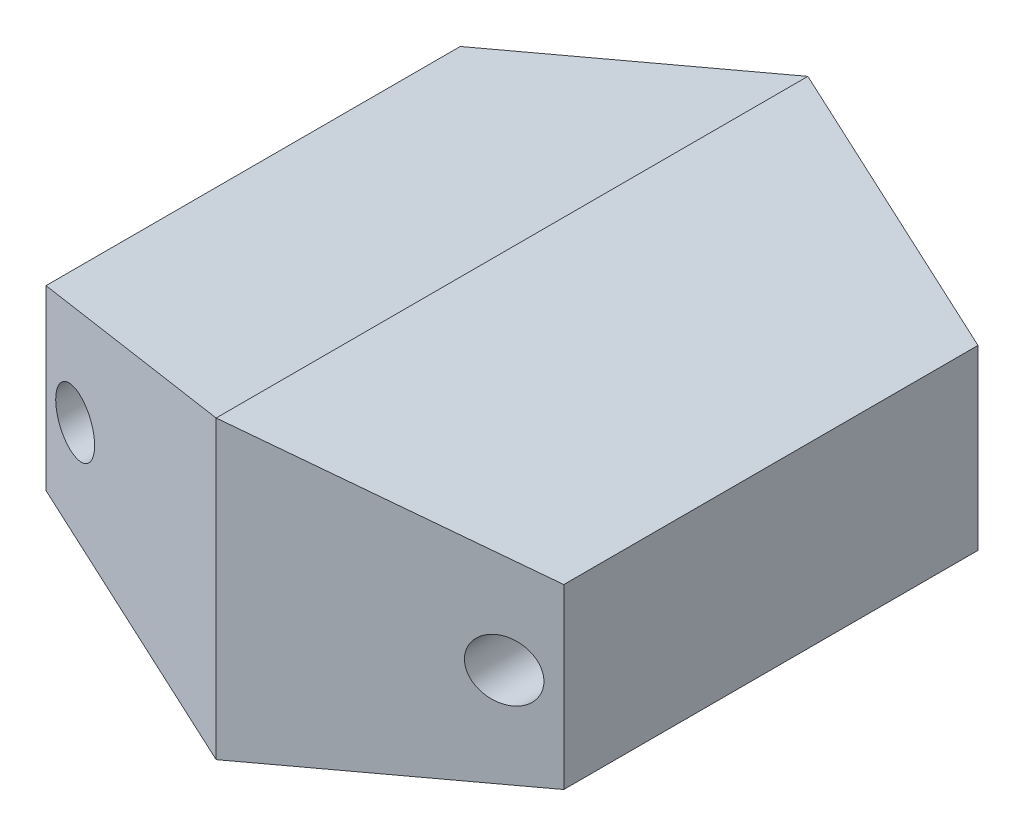
SolidWorks part; units mm, degrees
ref_plane "Front Plane" through (0, 0, 0) normal (0, 0, 1) x (1, 0, 0)
ref_plane "Top Plane" through (0, 0, 0) normal (0, 1, 0) x (1, 0, 0)
ref_plane "Right Plane" through (0, 0, 0) normal (1, 0, 0) x (0, 0, -1)
sketch "Sketch1" plane through (0, 0, 0) normal (0, 0, 1) x (1, 0, 0)
  line L1 (-17.5, -10) -> (17.5, -10)
  line L2 (-17.5, -10) -> (-17.5, 10)
  line L3 (-17.5, 10) -> (17.5, 10)
  line L4 (17.5, -10) -> (17.5, 10)
  line L5 (-17.5, -10) -> (17.5, 10) construction
  line L6 (-17.5, 10) -> (17.5, -10) construction
  point P0 (0, 0)
  dimension "D1" = 35
  dimension "D2" = 20
extrude "Boss-Extrude1" add sketch "Sketch1" along normal blind 40
sketch "Sketch2" plane through (0, 0, 40) normal (0, 0, 1) x (1, 0, 0)
  line L0 (0, 0) -> (0, 3.8546) construction
  line L1 (0, 0) -> (2.6656, 0) construction
  line L2 (0, 10) -> (-17.5, 6)
  line L3 (17.5, 10) -> (-17.5, 10) construction
  line L4 (-17.5, 10) -> (-17.5, -10) construction
  line L5 (0, 10) -> (17.5, 6)
  line L6 (0, -10) -> (17.5, -6)
  line L7 (0, -10) -> (-17.5, -6)
  dimension "D1" = 4
sketch "Sketch3" plane through (0, 0, 40) normal (0, 0, 1) x (1, 0, 0)
  line L0 (-17.5, 6) -> (-17.5, 10)
  line L1 (17.5, 10) -> (-17.5, 10) construction
  line L2 (-17.5, 10) -> (-17.5, -10) construction
  line L3 (-17.5, 10) -> (0, 10)
  line L4 (0, 10) -> (17.5, 10)
  line L5 (17.5, 10) -> (17.5, 6)
  line L6 (17.5, -6) -> (17.5, -10)
  line L7 (17.5, -10) -> (0, -10)
  line L8 (-17.5, -10) -> (17.5, -10) construction
  line L9 (0, -10) -> (-17.5, -10)
  line L10 (-17.5, -10) -> (-17.5, -6)
  line L11 (-17.5, 6) -> (0, 10)
  line L12 (0, 10) -> (17.5, 6)
  line L13 (17.5, -6) -> (0, -10)
  line L14 (0, -10) -> (-17.5, -6)
  line M1 (17.5, -10) -> (17.5, 10)
  line M2 (17.5, 10) -> (-17.5, 10)
  line M3 (-17.5, 10) -> (-17.5, -10)
  line M4 (-17.5, -10) -> (17.5, -10)
extrude "Cut-Extrude1" cut sketch "Sketch3" against normal blind 40 contours L11 M3 M2 | L12 M2 M1 | L13 M1 M4 | L14 M4 M3
sketch "Sketch5" plane through (0, 0, 0) normal (0, 1, 0) x (1, 0, 0)
  line L0 (0, 0) -> (0, -2.4045) construction
  line L1 (0, 0) -> (0, -40) construction
  line L2 (0, -20) -> (2.4073, -20) construction
  line L4 (0, 0) -> (-17.5, -6)
  line L5 (-17.5, 0) -> (-17.5, -40) construction
  line L6 (-17.5, 0) -> (0, 0) construction
  line L7 (0, 0) -> (17.5, -6)
  line L8 (0, -40) -> (17.5, -34)
  line L9 (0, -40) -> (-17.5, -34)
  line L10 (-17.5, -6) -> (-17.5, 0)
  line L11 (-17.5, 0) -> (0, 0)
  line L12 (17.5, -6) -> (17.5, 0)
  line L13 (17.5, 0) -> (0, 0)
  line L14 (17.5, -34) -> (17.5, -40)
  line L15 (17.5, -40) -> (0, -40)
  line L16 (0, -40) -> (-17.5, -40)
  line L17 (-17.5, -40) -> (-17.5, -34)
  dimension "D1" = 6
extrude "Cut-Extrude2" cut sketch "Sketch5" against normal through all both and the other way through all contours L11 L10 L4 | L12 L13 L7 | L15 L14 L8 | L17 L16 L9
sketch "Sketch6" plane through (0, 0, 0) normal (0, 0, 1) x (1, 0, 0)
  line L0 (0, 0) -> (0, 2.819) construction
  line L1 (0, -10) -> (0, 10) construction
  line L2 (-17.5, -6) -> (-17.5, 6) construction
  circle A0 centre (-14.5, 0) radius 2
  circle A1 centre (14.5, 0) radius 2
  dimension "D1" = 3
extrude "Cut-Extrude3" cut sketch "Sketch6" along normal through all
